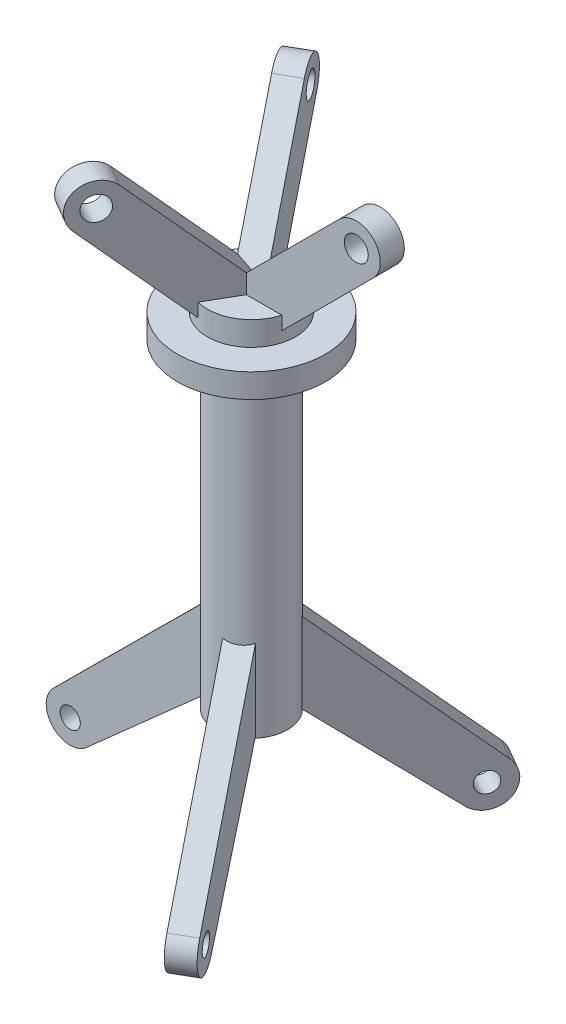
SolidWorks part; units mm, degrees
material "Commercially Pure CP-Ti UNS R50400 (SS)"
ref_plane "Front Plane" through (0, 0, 0) normal (0, 0, 1) x (1, 0, 0)
ref_plane "Top Plane" through (0, 0, 0) normal (0, 1, 0) x (1, 0, 0)
ref_plane "Right Plane" through (0, 0, 0) normal (1, 0, 0) x (0, 0, -1)
sketch "Sketch2" plane through (0, 0, 0) normal (0, 0, 1) x (1, 0, 0)
  line L0 (0, 107.5) -> (0, -107.5) construction
  line L1 (22.5, -107.5) -> (22.5, 92.5)
  line L2 (22.5, 92.5) -> (46.2, 92.5)
  line L3 (46.2, 92.5) -> (46.2, 107.5)
  line L4 (46.2, 107.5) -> (17.5, 107.5)
  line L5 (17.5, 107.5) -> (17.5, -107.5)
  line L6 (17.5, -107.5) -> (22.5, -107.5)
  dimension "D1" = 215
  dimension "D2" = 15
  dimension "D3" = 5
  dimension "D4" = 22.5
  dimension "D5" = 23.7
revolve "Revolve1" add sketch "Sketch2" angle 360 about L0
sketch "Sketch3" plane through (0, 0, 0) normal (0, 0, 1) x (1, 0, 0)
  line L1 (-22.5, 92.5) -> (-22.5, -107.5) construction
  line L3 (-89.3934, -174.3934) -> (-22.5, -107.5) construction
  line L5 (0, 92.5) -> (0, -210.5514) construction
  line L6 (-22.5, 92.5) -> (22.5, 92.5) construction
  line L7 (-95.7221, -172.5) -> (-22.5, -107.5)
  line L8 (-22.5, -107.5) -> (22.5, -107.5) construction
  line L10 (-105.6802, -161.2823) -> (-116.2521, -150.6411) construction
  line L11 (-116.2521, -150.6411) -> (-105.6802, -161.2823) construction
  line L12 (-105.6802, -161.2823) -> (-95.7221, -172.5) construction
  line L13 (-116.2521, -150.6411) -> (-22.5, -57.5)
  line L14 (-19.5, -57.5) -> (-19.5, -105.5603)
  line L15 (-22.5, -107.5) -> (-19.5, -105.5603)
  line L16 (-19.5, -57.5) -> (-19.5, -54.5196)
  line L17 (-22.5, -57.5) -> (-19.5, -54.5196)
  arc A0 (-116.2521, -150.6411) -> (-95.7221, -172.5) centre (-105.6802, -161.2823) ccw
  circle A1 centre (-105.6802, -161.2823) radius 6.3
  dimension "D4" = 30
  dimension "D6" = 12.6
  dimension "D1" = 45
  dimension "D3" = 50
  dimension "D5" = 65
  dimension "D7" = 83.1802
extrude "Boss-Extrude1" add sketch "Sketch3" along normal mid plane 15 separate body
pattern_circular "CirPattern2" count 3 over 360 about axis through (0, 0, 0) along (0, 1, 0) of bodies 103
sketch "Sketch4" plane through (0, 107.5, 0) normal (0, 1, 0) x (1, 0, 0)
  circle A0 centre (0, 0) radius 17.5 construction
  circle A1 centre (0, 0) radius 46.2
  circle A2 centre (0, 0) radius 46.2
  circle A3 centre (0, 0) radius 17.5
  circle M2 centre (0, 0) radius 17.5
  dimension "D1" = 0
extrude "Boss-Extrude2" add sketch "Sketch4" against normal blind 15 contours M2
sketch "Sketch6" plane through (0, 0, 0) normal (0, 0, 1) x (1, 0, 0)
  line L0 (-21.4655, 108.5345) -> (62.3528, 192.3528)
  line L1 (62.3528, 192.3528) -> (83.566, 171.1396) construction
  line L2 (83.566, 171.1396) -> (19.9264, 107.5)
  line L3 (46.2, 107.5) -> (-46.2, 107.5) construction
  line L4 (19.9264, 107.5) -> (-22.5, 107.5)
  line L5 (-22.5, 107.5) -> (-21.4655, 108.5345)
  arc A0 (62.3528, 192.3528) -> (83.566, 171.1396) centre (72.9594, 181.7462) cw
  circle A1 centre (72.9594, 181.7462) radius 7.5
  dimension "D1" = 15
  dimension "D5" = 15
  dimension "D2" = 120
  dimension "D3" = 45
  dimension "D4" = 23.7
extrude "Boss-Extrude3" add sketch "Sketch6" along normal mid plane 15
pattern_circular "CirPattern3" count 3 over 360 about axis through (0, 0, 0) along (0, 1, 0) of bodies 108
sketch "Sketch7" plane through (0, 107.5, 0) normal (0, 1, 0) x (1, 0, 0)
  circle A0 centre (0, 0) radius 27.5
  dimension "D1" = 55
extrude "Boss-Extrude4" add sketch "Sketch7" along normal blind 15
